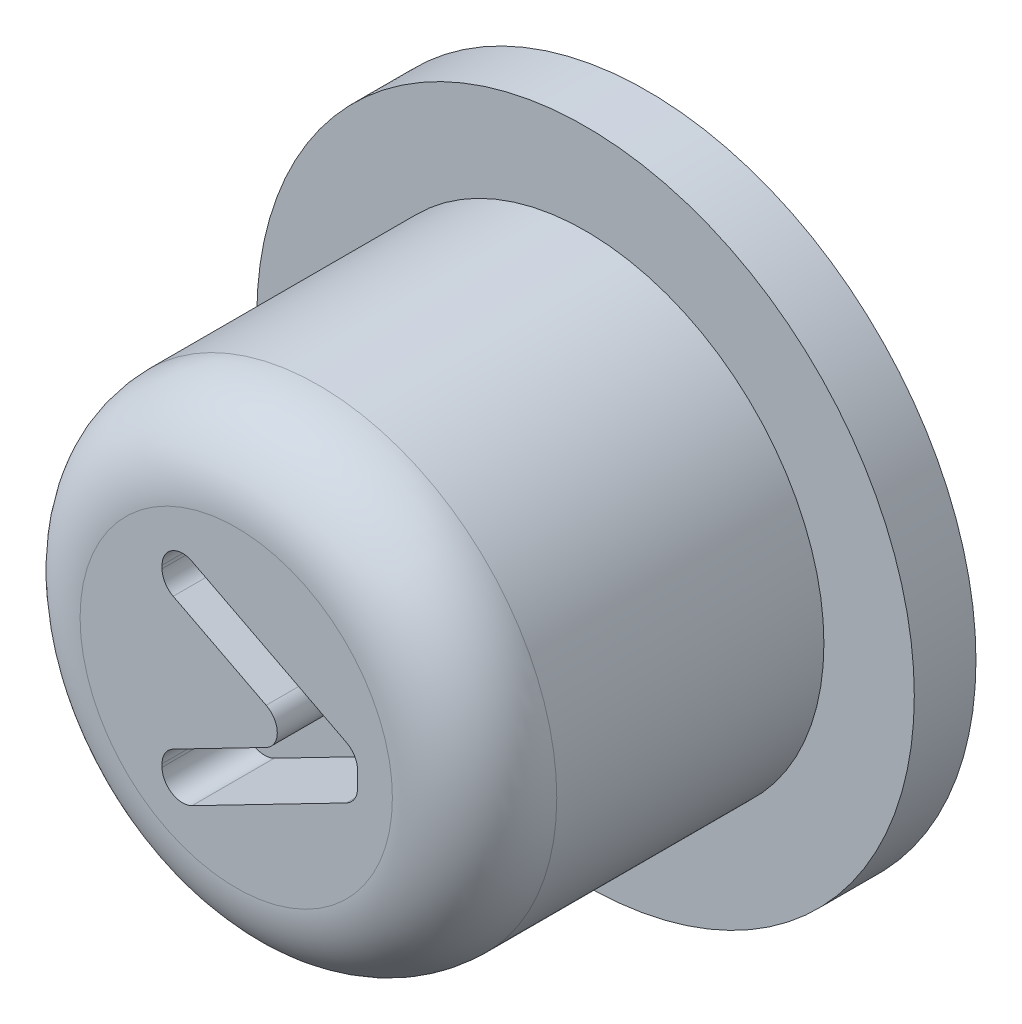
SolidWorks part; units mm, degrees
material "ABS"
ref_plane "Płaszczyzna przednia" through (0, 0, 0) normal (0, 0, 1) x (1, 0, 0)
ref_plane "Płaszczyzna górna" through (0, 0, 0) normal (0, 1, 0) x (1, 0, 0)
ref_plane "Płaszczyzna prawa" through (0, 0, 0) normal (1, 0, 0) x (0, 0, -1)
sketch "Szkic1" plane through (0, 0, 0) normal (0, 0, 1) x (1, 0, 0)
  circle A0 centre (0, 0) radius 4
  dimension "D1" = 8
extrude "Dodanie-wyciągnięcie1" add sketch "Szkic1" along normal blind 0.75
sketch "Szkic2" plane through (0, 0, 0.75) normal (0, 0, 1) x (1, 0, 0)
  circle A0 centre (0, 0) radius 2.9
  dimension "D1" = 5.8
extrude "Dodanie-wyciągnięcie2" add sketch "Szkic2" along normal blind 4.25
sketch "Szkic3" plane through (0, 0, 0) normal (0, 0, -1) x (-1, 0, 0)
  line L1 (-1.25, 1.25) -> (1.25, 1.25)
  line L2 (-1.25, 1.25) -> (-1.25, -1.25)
  line L3 (-1.25, -1.25) -> (1.25, -1.25)
  line L4 (1.25, 1.25) -> (1.25, -1.25)
  line L5 (-1.25, 1.25) -> (1.25, -1.25) construction
  line L6 (-1.25, -1.25) -> (1.25, 1.25) construction
  point P0 (0, 0)
  dimension "D1" = 2.5
extrude "Wytnij-wyciągnięcie1" cut sketch "Szkic3" against normal blind 1
fillet "Zaokrąglenie1" [suppressed] radius 1
fillet "Zaokrąglenie2" radius 1 1 edges at (2.9, 0, 5)
sketch "Szkic4" plane through (0, 0, 0) normal (0, 0, -1) x (-1, 0, 0)
  line L8 (1.45, 1.45) -> (-1.45, 1.45)
  line L9 (-1.45, 1.45) -> (-1.45, -1.45)
  line L10 (-1.45, -1.45) -> (1.45, -1.45)
  line L11 (1.45, -1.45) -> (1.45, 1.45)
  line L12 (1.45, 1.45) -> (-1.45, 1.45)
  line L13 (-1.45, 1.45) -> (-1.45, -1.45)
  line L14 (-1.45, -1.45) -> (1.45, -1.45)
  line L15 (1.45, -1.45) -> (1.45, 1.45)
  dimension "D1" = 0.2
extrude "Wytnij-wyciągnięcie2" cut sketch "Szkic4" against normal up to surface (1 mm away) up to face at (0, 0, 1)
sketch "Szkic5" plane through (0, 0, 5) normal (0, 0, 1) x (1, 0, 0)
  text T0 "<b>></b>"
  point P1 (0, 0)
  point P2 (-1.1714, -1.7423)
extrude "Wytnij-wyciągnięcie3" cut sketch "Szkic5" against normal blind 1
fillet "Zaokrąglenie3" radius 0.25 7 edges at (1.476, 0.2342, 4.5) (1.476, -0.2636, 4.5) (-0.9022, -1.4892, 4.5) (-0.9022, 1.4604, 4.5) (-0.9022, 0.8603, 4.5) (-0.9022, -0.8897, 4.5) (0.7952, -0.0147, 4.5)
